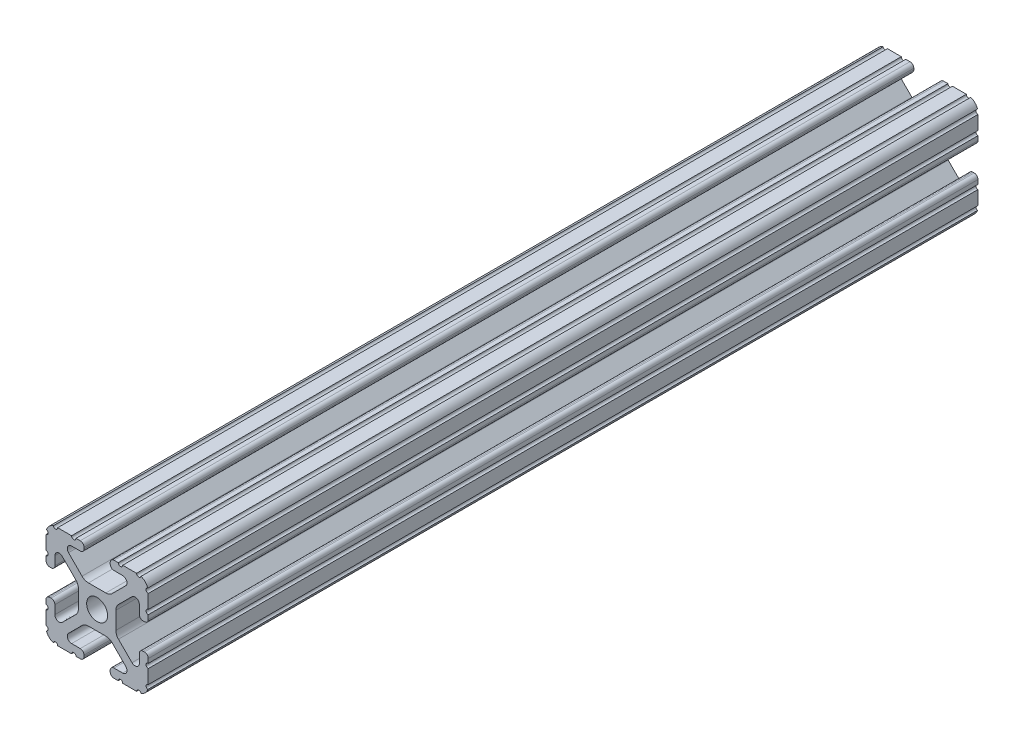
SolidWorks part; units mm, degrees
ref_plane "Front Plane" through (0, 0, 0) normal (0, 0, 1) x (1, 0, 0)
ref_plane "Top Plane" through (0, 0, 0) normal (0, 1, 0) x (1, 0, 0)
ref_plane "Right Plane" through (0, 0, 0) normal (1, 0, 0) x (0, 0, -1)
sketch "Sketch2" plane through (0, 0, 0) normal (0, 0, 1) x (1, 0, 0)
  line L0 (0, 12.7) -> (0, -12.7) construction
  line L1 (-12.7, 0) -> (12.7, 0) construction
  line L2 (3.2512, -12.7) -> (12.7, -12.7)
  line L3 (12.7, -12.7) -> (12.7, -3.2512)
  line L4 (3.2512, -12.7) -> (3.2512, -10.4902)
  line L5 (3.2512, -10.4902) -> (8.9276, -10.4902)
  line L6 (8.9276, -10.4902) -> (3.0856, -4.6482)
  line L7 (0, 0) -> (12.7, -12.7) construction
  line L8 (12.7, -3.2512) -> (10.4902, -3.2512)
  line L9 (10.4902, -3.2512) -> (10.4902, -8.9276)
  line L10 (10.4902, -8.9276) -> (4.6482, -3.0856)
  circle A0 centre (0, 0) radius 2.6035
  arc A1 (6.3485, -10.4902) -> (7.1039, -8.6665) centre (6.3485, -9.4219) ccw construction
  point P8 (0, -4.6482)
  dimension "Center Hole Diameter" = 5.207
  dimension "Rail Height" = 25.4
  dimension "Rail Width" = 25.4
  dimension "T-Slot Width" = 6.5024
  dimension "Slot Inner Width" = 14.8336
  dimension "Thickness" = 2.2098
  dimension "Slot Depth" = 5.842
  dimension "D1" = 2.2098
sketch "Sketch3" plane through (0, 0, 0) normal (1, 0, 0) x (0, 0, -1)
  line L0 (-103.0606, -12.7) -> (103.0606, -12.7) construction
  line L1 (-77.6606, 0) -> (77.6606, 0) construction
  line L4 (103.0606, 0) -> (-103.0606, 0) construction
  point P5 (-38.2187, -12.7)
sketch "Sketch4" plane through (0, 0, 0) normal (0, 0, 1) x (1, 0, 0)
  line L0 (4.1904, -12.7) -> (10.1173, -12.7)
  line L1 (3.2512, -12.7) -> (12.7, -12.7) construction
  line L2 (3.2512, -12.7) -> (3.2512, -10.4902) construction
  line L3 (3.2512, -10.4902) -> (8.9276, -10.4902) construction
  line L4 (3.2512, -11.4294) -> (3.2512, -11.7608)
  line L5 (4.1904, -10.4902) -> (6.3485, -10.4902)
  line L6 (0, -4.6482) -> (2.164, -4.6482)
  line L7 (8.9276, -10.4902) -> (3.0856, -4.6482) construction
  line L8 (3.7373, -5.2999) -> (7.1039, -8.6665)
  line L9 (12.7, -12.7) -> (12.7, -3.2512) construction
  line L10 (10.4902, -8.9276) -> (4.6482, -3.0856) construction
  line L11 (10.4902, -3.2512) -> (10.4902, -8.9276) construction
  line L12 (10.4902, -6.3485) -> (10.4902, -4.1904)
  line L13 (12.7, -3.2512) -> (10.4902, -3.2512) construction
  line L14 (11.4294, -3.2512) -> (11.7608, -3.2512)
  line L15 (12.7, -4.1904) -> (12.7, -10.1173)
  line L16 (8.6665, -7.1039) -> (5.2999, -3.7373)
  line L17 (4.6482, 0) -> (4.6482, -2.164)
  line L18 (-12.7, 0) -> (12.7, 0) construction
  line L19 (0, -4.6482) -> (0, -2.6035)
  line L20 (0, 12.7) -> (0, -12.7) construction
  line L21 (4.6482, 0) -> (2.6035, 0)
  arc A0 (3.2512, -11.7608) -> (4.1904, -12.7) centre (4.1904, -11.7608) ccw
  arc A2 (3.2512, -11.4294) -> (4.1904, -10.4902) centre (4.1904, -11.4294) cw
  arc A3 (6.3485, -10.4902) -> (7.1039, -8.6665) centre (6.3485, -9.4219) ccw
  arc A4 (2.164, -4.6482) -> (3.7373, -5.2999) centre (2.164, -6.8732) cw
  arc A5 (10.1173, -12.7) -> (12.7, -10.1173) centre (10.1173, -10.1173) ccw
  arc A6 (8.6665, -7.1039) -> (10.4902, -6.3485) centre (9.4219, -6.3485) ccw
  arc A7 (10.4902, -4.1904) -> (11.4294, -3.2512) centre (11.4294, -4.1904) cw
  arc A8 (11.7608, -3.2512) -> (12.7, -4.1904) centre (11.7608, -4.1904) cw
  arc A9 (5.2999, -3.7373) -> (4.6482, -2.164) centre (6.8732, -2.164) cw
  circle A10 centre (0, 0) radius 2.6035 construction
  arc A11 (0, -2.6035) -> (2.6035, 0) centre (0, 0) ccw
  dimension "D1" = 2.5827
  dimension "D2" = 2.225
  dimension "D3" = 0.9392
extrude "Boss-Extrude1" add sketch "Sketch4" along normal up to vertex (103.0606 mm away) from vertex at -103.0606 starting at point (0, -12.7, -103.0606)
sketch "Sketch5" plane through (0, 0, 0) normal (0, 0, 1) x (1, 0, 0)
  line L0 (3.2512, -12.7) -> (12.7, -12.7) construction
  line L1 (4.1904, -10.4902) -> (6.3485, -10.4902) construction
  line L3 (0, 0) -> (12.7, -12.7) construction
  line L4 (6.3485, -10.4902) -> (6.3485, -12.7) construction
  line L5 (8.9276, -10.4902) -> (3.0856, -4.6482) construction
  circle A0 centre (10.3562, -12.7) radius 0.5524
  circle A1 centre (5.796, -12.7) radius 0.5524
  circle A2 centre (12.7, -10.3562) radius 0.5524
  circle A3 centre (12.7, -5.796) radius 0.5524
  point P10 (5.2694, -10.4902)
  point P12 (9.4219, -6.3485)
  dimension "D1" = 1.1049
extrude "Cut-Extrude1" cut sketch "Sketch5" against normal through all both and the other way through all
mirror "Mirror1" about plane through (0, 0, 0) normal (1, 0, 0) of bodies 137 134
mirror "Mirror2" about plane through (0, 0, 0) normal (0, 1, 0) of bodies 135
equation "\"D1@Sketch2\"=\"Thickness@Sketch2\""
equation "\"D2@Sketch4\"=\"Slot Inner Width@Sketch2\"*0.15"
equation "\"D1@Sketch4\"=\"D3@Sketch4\"*2.75"
equation "\"D3@Sketch4\"=\"Thickness@Sketch2\"*0.425"
equation "\"D1@Sketch5\"=\"Thickness@Sketch2\"*0.5"
equation "\"D1@Boss-Extrude1\"=\"Length@Sketch3\""
